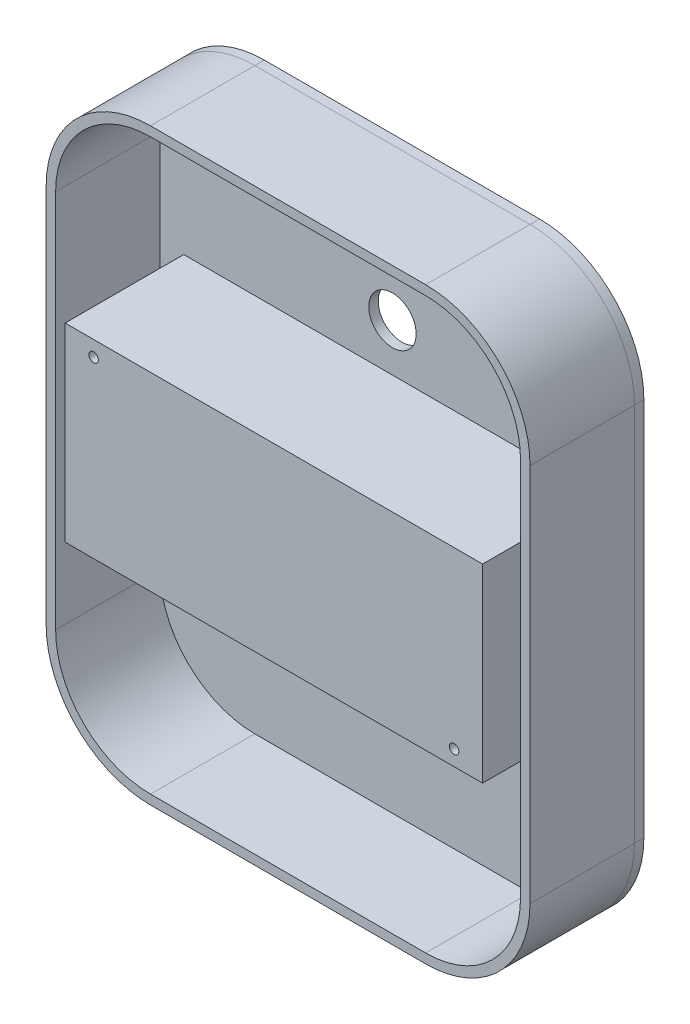
SolidWorks part; units mm, degrees
ref_plane "Front Plane" through (0, 0, 0) normal (0, 0, 1) x (1, 0, 0)
ref_plane "Top Plane" through (0, 0, 0) normal (0, 1, 0) x (1, 0, 0)
ref_plane "Right Plane" through (0, 0, 0) normal (1, 0, 0) x (0, 0, -1)
sketch "Sketch1" plane through (0, 0, 0) normal (0, 0, 1) x (1, 0, 0)
  line L0 (0, 60) -> (0, -60) construction
  line L5 (-29, 60) -> (29, 60)
  line L6 (-49, 40) -> (-49, -40)
  line L7 (-29, -60) -> (29, -60)
  line L8 (49, 40) -> (49, -40)
  line L9 (-49, 0) -> (49, 0) construction
  line L10 (-29, 62) -> (29, 62)
  line L11 (51, 40) -> (51, -40)
  line L12 (-29, -62) -> (29, -62)
  line L13 (-51, 40) -> (-51, -40)
  arc A2 (49, 40) -> (29, 60) centre (29, 40) ccw
  arc A3 (49, -40) -> (29, -60) centre (29, -40) cw
  arc A4 (-29, -60) -> (-49, -40) centre (-29, -40) cw
  arc A5 (-49, 40) -> (-29, 60) centre (-29, 40) cw
  arc A6 (51, 40) -> (29, 62) centre (29, 40) ccw
  arc A7 (51, -40) -> (29, -62) centre (29, -40) cw
  arc A8 (-29, -62) -> (-51, -40) centre (-29, -40) cw
  arc A9 (-51, 40) -> (-29, 62) centre (-29, 40) cw
  point P17 (49, 60)
  point P23 (-49, -60)
  point P26 (-49, 60)
  dimension "D5" = 20
  dimension "D3" = 98
  dimension "D4" = 120
  dimension "D6" = 2
extrude "Boss-Extrude1" add sketch "Sketch1" along normal blind 22
sketch "Sketch3" plane through (0, 0, 0) normal (0, 0, 1) x (1, 0, 0)
  line L0 (-44, -20) -> (-44, 20)
  line L1 (-44, -20) -> (44, -20)
  line L2 (44, -20) -> (44, 20)
  line L3 (-44, 20) -> (44, 20)
  line L4 (-44, 0) -> (44, 0) construction
  line L5 (0, 20) -> (0, -20) construction
  line L6 (-38, 16.75) -> (-38, 0) construction
  line L7 (38, -16.75) -> (38, 0) construction
  line L8 (-38, 16.75) -> (0, 16.75) construction
  line L9 (38, -16.75) -> (0, -16.75) construction
  circle A3 centre (-38, 16.75) radius 1
  circle A4 centre (38, -16.75) radius 1
  dimension "D5" = 2
  dimension "D1" = 88
  dimension "D2" = 40
  dimension "D3" = 76
  dimension "D4" = 33.5
extrude "Boss-Extrude2" add sketch "Sketch3" along normal blind 25
sketch "Sketch6" plane through (0, 0, 0) normal (0, 0, 1) x (1, 0, 0)
  line L0 (-29, 62) -> (29, 62)
  line L1 (51, 40) -> (51, -40)
  line L2 (-29, -62) -> (29, -62)
  line L3 (-51, 40) -> (-51, -40)
  line L6 (0, 0) -> (7.7555, 0) construction
  arc A0 (51, 40) -> (29, 62) centre (29, 40) ccw
  arc A1 (51, -40) -> (29, -62) centre (29, -40) cw
  arc A2 (-29, -62) -> (-51, -40) centre (-29, -40) cw
  arc A3 (-51, 40) -> (-29, 62) centre (-29, 40) cw
  circle A4 centre (0, 41) radius 1.75
  circle A5 centre (0, -41) radius 1.75
  circle A6 centre (0, 30) radius 5
  circle A7 centre (0, -30) radius 5
  point P22 (0, 0)
  point P23 (0, 0)
  dimension "D2" = 3.5
  dimension "D3" = 10
  dimension "D1" = 82
  dimension "D4" = 30
extrude "Boss-Extrude3" add sketch "Sketch6" against normal blind 2
sketch "Sketch4" plane through (0, 0, 0) normal (0, 0, 1) x (1, 0, 0)
  line L1 (-37.5, 55) -> (37.5, 55)
  line L2 (-37.5, 55) -> (-37.5, -55)
  line L3 (-37.5, -55) -> (37.5, -55)
  line L4 (37.5, 55) -> (37.5, -55)
  line L5 (-28.5, 50) -> (28.5, 50)
  line L6 (-28.5, 50) -> (-28.5, -50)
  line L7 (-28.5, -50) -> (28.5, -50)
  line L8 (28.5, 50) -> (28.5, -50)
  point P4 (-37.5, 0)
  point P6 (0, 55)
  point P11 (0, 50)
  point P12 (-28.5, 0)
  dimension "D1" = 75
  dimension "D2" = 110
  dimension "D3" = 57
  dimension "D4" = 100
